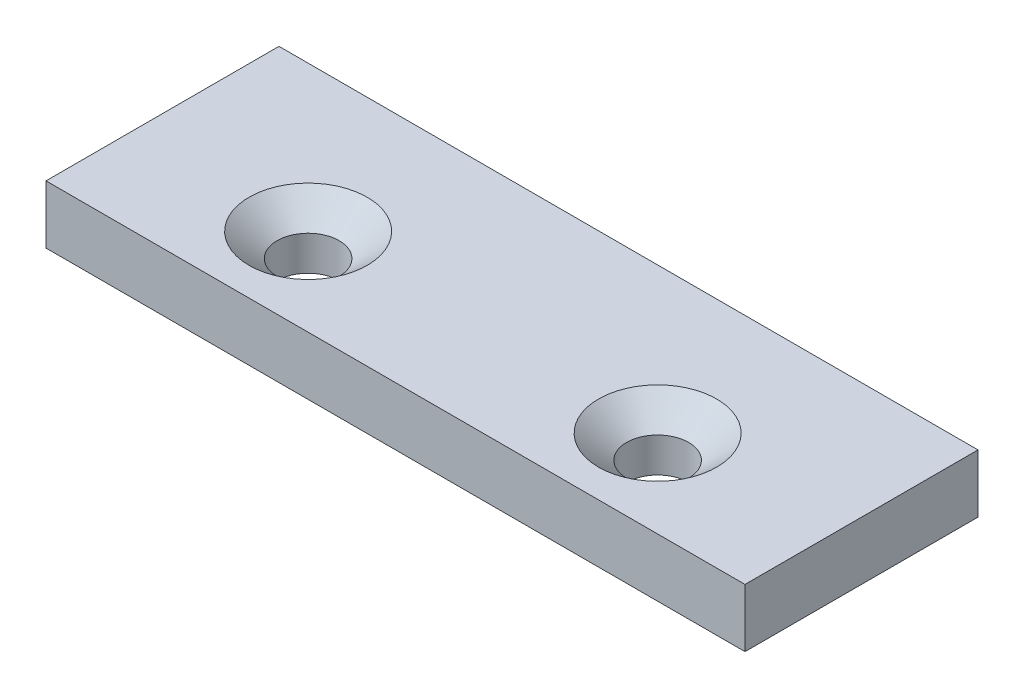
SolidWorks part; units mm, degrees
material "6061 Alloy"
ref_plane "Front Plane" through (0, 0, 0) normal (0, 0, 1) x (1, 0, 0)
ref_plane "Top Plane" through (0, 0, 0) normal (0, 1, 0) x (1, 0, 0)
ref_plane "Right Plane" through (0, 0, 0) normal (1, 0, 0) x (0, 0, -1)
sketch "Sketch1" plane through (0, 0, 0) normal (0, 1, 0) x (1, 0, 0)
  line L1 (0, 0) -> (76.2, 0)
  line L2 (0, 0) -> (0, 25.4)
  line L3 (0, 25.4) -> (76.2, 25.4)
  line L4 (76.2, 0) -> (76.2, 25.4)
  point P5 (57.15, 9.525)
  point P8 (19.05, 9.525)
  dimension "D1" = 25.4
  dimension "D2" = 76.2
  dimension "D3" = 19.05
  dimension "D4" = 9.525
  dimension "D5" = 19.05
  dimension "D6" = 9.525
extrude "Boss-Extrude1" add sketch "Sketch1" against normal blind 6.35
hole_wizard "CSK for 1/4 Flat Head Machine Screw (100)1" positions "Sketch2" profile "Sketch3" countersink size "1/4" standard "ANSI Inch" end condition through all
sketch "Sketch2" plane through (0, 0, 0) normal (0, 1, 0) x (1, 0, 0)
  line L0 (0, 0) -> (76.2, 0) construction
  line L1 (0, 25.4) -> (0, 0) construction
  line L2 (76.2, 0) -> (76.2, 25.4) construction
  point P0 (19.05, 9.525)
  point P2 (57.15, 9.525)
  dimension "D1" = 9.525
  dimension "D2" = 9.525
  dimension "D3" = 19.05
  dimension "D4" = 19.05
sketch "Sketch3" plane through (19.05, 0, -9.525) normal (1, 0, 0) x (0, 0, 1)
  line L0 (0, 0) -> (0, 6.35)
  line L1 (0, 6.35) -> (3.3782, 6.35)
  line L2 (3.3782, 6.35) -> (3.3782, 2.5682)
  line L3 (3.3782, 2.5682) -> (6.4389, 0)
  line L5 (6.4389, 0) -> (0, 0)
  line L6 (-3.3782, 2.5682) -> (-6.4389, 0) construction
  line L11 (0, -6.35) -> (0, 107.95) construction
  dimension "Thru Hole Dia." = 6.7564
  dimension "Thru Hole Depth" = 6.35
  dimension "Near C'Sink Dia." = 12.8778
  dimension "Near C'Sink Angle" = 100
